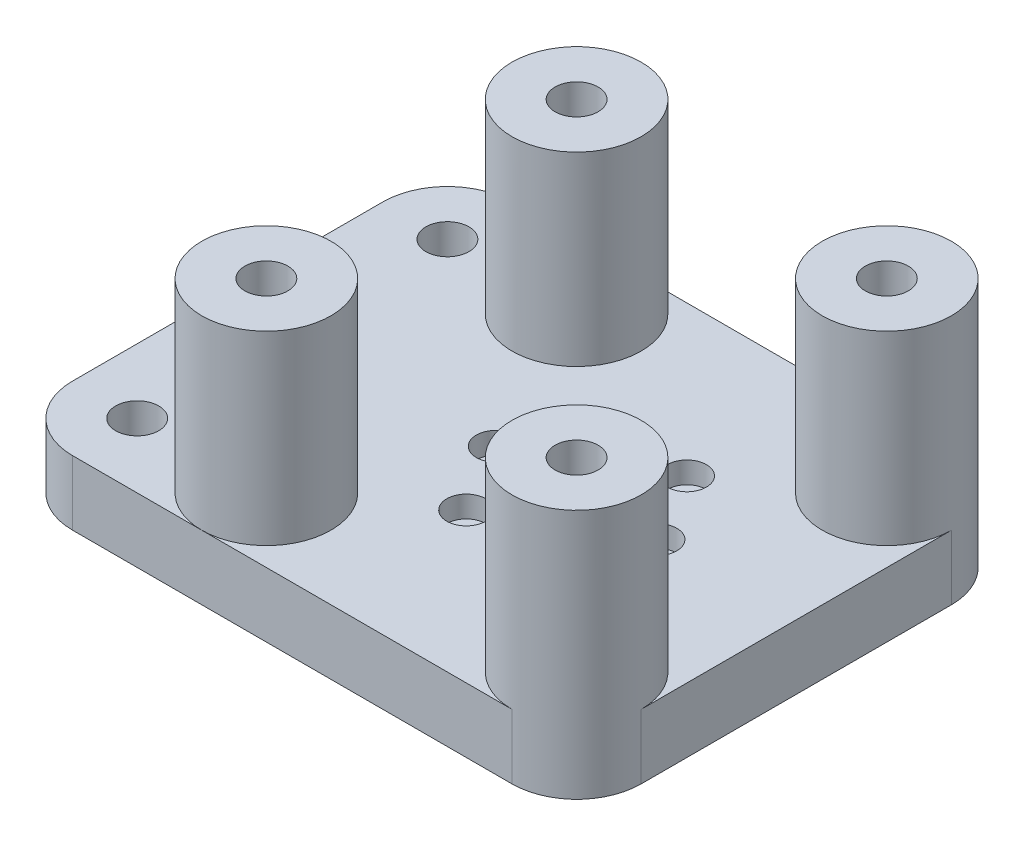
SolidWorks part; units mm, degrees
material "1060 Alloy"
ref_plane "Front" through (0, 0, 0) normal (0, 0, 1) x (1, 0, 0)
ref_plane "Top" through (0, 0, 0) normal (0, 1, 0) x (1, 0, 0)
ref_plane "Right" through (0, 0, 0) normal (1, 0, 0) x (0, 0, -1)
sketch "Sketch1" plane through (0, 0, 0) normal (0, 1, 0) x (1, 0, 0)
  line L0 (0, 0) -> (-28.8146, 28.8146) construction
  line L1 (-52.8146, 40.8146) -> (28.8146, 40.8146)
  line L2 (0, 0) -> (-7.5, 12.9904) construction
  line L3 (-52.8146, -40.8146) -> (28.8146, -40.8146)
  line L4 (-64.8146, 28.8146) -> (-64.8146, -28.8146)
  line L8 (40.8146, 28.8146) -> (40.8146, -28.8146)
  circle A0 centre (-28.8146, 28.8146) radius 4
  circle A1 centre (28.8146, 28.8146) radius 4
  circle A2 centre (28.8146, -28.8146) radius 4
  circle A3 centre (-28.8146, -28.8146) radius 4
  circle A4 centre (0, 0) radius 10.5
  circle A5 centre (-52.8146, 28.8146) radius 12 construction
  arc A6 (40.8146, 28.8146) -> (28.8146, 40.8146) centre (28.8146, 28.8146) ccw
  arc A7 (28.8146, -40.8146) -> (40.8146, -28.8146) centre (28.8146, -28.8146) ccw
  circle A8 centre (-28.8146, 28.8146) radius 12 construction
  circle A21 centre (0, 0) radius 15 construction
  circle A22 centre (-7.5, 12.9904) radius 2
  circle A23 centre (7.5, 12.9904) radius 2
  circle A24 centre (15, 0) radius 2
  circle A25 centre (7.5, -12.9904) radius 2
  circle A26 centre (-7.5, -12.9904) radius 2
  circle A27 centre (-15, 0) radius 2
  circle A30 centre (-52.8146, 28.8146) radius 4
  circle A31 centre (-52.8146, -28.8146) radius 4
  arc A32 (-64.8146, -28.8146) -> (-52.8146, -40.8146) centre (-52.8146, -28.8146) ccw
  arc A33 (-52.8146, 40.8146) -> (-64.8146, 28.8146) centre (-52.8146, 28.8146) ccw
  point P0 (0, 0)
  point P17 (0, 0)
  point P27 (0, 0)
  point P56 (0, 0)
  dimension "D5" = 8
  dimension "D6" = 21
  dimension "D9" = 30
  dimension "D11" = 4
  dimension "D8" = 12
  dimension "D3" = 40.75
  dimension "D2" = 12
  dimension "D7" = 12
  dimension "D4" = 4
  dimension "D12" = 6
extrude "base" add sketch "Sketch1" along normal blind 12
sketch "Sketch2" plane through (0, 12, 0) normal (0, 1, 0) x (1, 0, 0)
  circle A0 centre (0, 0) radius 15 construction
  circle A1 centre (-7.5, 12.9904) radius 3.625
  circle A2 centre (7.5, 12.9904) radius 3.625
  circle A3 centre (15, 0) radius 3.625
  circle A4 centre (7.5, -12.9904) radius 3.625
  circle A5 centre (-7.5, -12.9904) radius 3.625
  circle A7 centre (-15, 0) radius 3.625
  point P15 (0, 0)
  point P17 (0, 0)
  dimension "D1" = 7.25
  dimension "D2" = 6
extrude "bolt head recesses" cut sketch "Sketch2" against normal blind 4
sketch "Sketch3" plane through (0, 12, 0) normal (0, 1, 0) x (1, 0, 0)
  line L0 (28.8146, 40.8146) -> (-52.8146, 40.8146) construction
  line L1 (-52.8146, -40.8146) -> (28.8146, -40.8146) construction
  circle A0 centre (-28.8146, 28.8146) radius 12
  circle A1 centre (28.8146, 28.8146) radius 12
  circle A2 centre (28.8146, -28.8146) radius 12
  circle A3 centre (-28.8146, -28.8146) radius 12
  circle A4 centre (-28.8146, 28.8146) radius 4
  circle A5 centre (-28.8146, 28.8146) radius 4 construction
  circle A6 centre (28.8146, 28.8146) radius 4
  circle A7 centre (28.8146, -28.8146) radius 4
  circle A8 centre (-28.8146, -28.8146) radius 4
  point P14 (0, 0)
  point P26 (0, 0)
  dimension "D1" = 4
  dimension "D2" = 4
extrude "Boss-Extrude1" add sketch "Sketch3" along normal blind 34.5
equation "\"D3@Sketch1\"=\"square plate bolt pattern diameter\"/2"
equation "\"D1@base\" = \"motor mount plate thickness\""
equation "\"D5@Sketch1\" = \"square plate bolt bore\""
equation "\"D6@Sketch1\"=\"coupler OD\"+4mm"
equation "\"coupler motor shaft hole ID\"= 8mm"
equation "\"coupler OD\"= 17mm"
equation "\"coupler length\"= 25mm"
equation "\"square plate bolt pattern diameter\"= \"motor OD\" + \"square plate bolt head diameter\" + 4mm"
equation "\"motor mount m4 screw hole diameter\"= 4mm"
equation "\"motor mount m4 head diameter\"= 7.25mm"
equation "\"motor mount m4 head depth\"= 4mm"
equation "\"motor mount plate thickness\"= 8mm + \"motor mount m4 head depth\""
equation "\"motor shaft pride\"= 32mm"
equation "\"D7@Sketch1\"=\"motor mount post radius\""
equation "\"motor mount m4 pattern diamater\"= 30mm"
equation "\"D9@Sketch1\"=\"motor mount m4 pattern diamater\""
equation "\"D11@Sketch1\"=\"motor mount m4 screw hole diameter\""
equation "\"D1@Sketch2\"=\"motor mount m4 head diameter\""
equation "\"D1@bolt head recesses\" = \"motor mount m4 head depth\""
equation "\"motor OD\"= 64mm"
equation "\"square plate bolt bore\"= 8mm"
equation "\"square plate bolt head diameter\"= 13.5mm"
equation "\"motor to bearing plate distance\"= \"motor shaft pride\" + 2mm +\"coupler length\"/2"
equation "\"motor mount center bore\"= \"coupler OD\"+ 4mm"
equation "\"motor mount post radius\"= ( 3 * \"square plate bolt bore\" ) / 2"
equation "\"motor shaft diameter\"= 8mm"
equation "\"D2@Sketch1\"=\"motor mount post radius\""
equation "\"D8@Sketch1\"=\"motor mount post radius\""
equation "\"D1@Boss-Extrude1\"=\"motor to bearing plate distance\"-\"motor mount plate thickness\""
